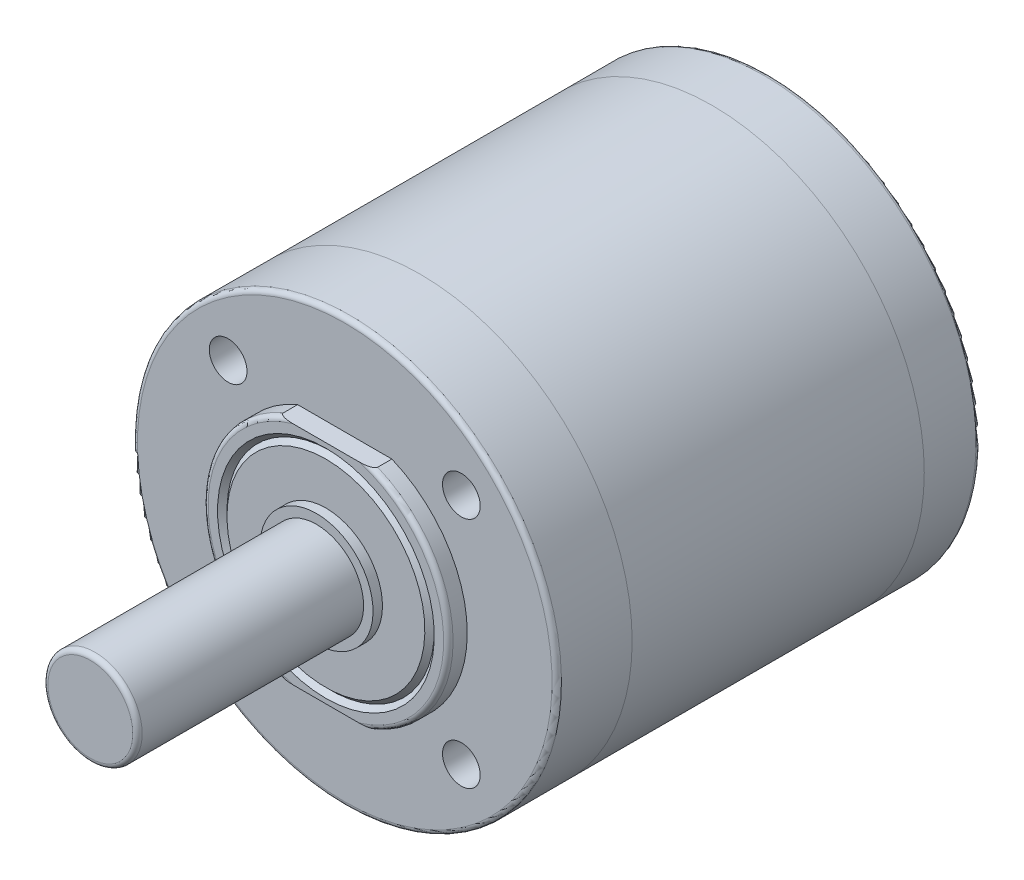
SolidWorks part; units mm, degrees
ref_plane "Front Plane" through (0, 0, 0) normal (0, 0, 1) x (1, 0, 0)
ref_plane "Top Plane" through (0, 0, 0) normal (0, 1, 0) x (1, 0, 0)
ref_plane "Right Plane" through (0, 0, 0) normal (1, 0, 0) x (0, 0, -1)
sketch "Sketch1" plane through (0, 0, 0) normal (1, 0, 0) x (0, 0, -1)
  line L0 (0, 0) -> (-72, 0) construction
  line L1 (0, 0) -> (0, 22.5)
  line L2 (0, 22.5) -> (-45, 22.5)
  line L3 (-45, 22.5) -> (-45, 13)
  line L4 (-45, 13) -> (-47, 13)
  line L5 (-47, 13) -> (-47, 11.5)
  line L6 (-48, 5) -> (-72, 5)
  line L7 (-72, 5) -> (-72, 0)
  line L8 (0, 0) -> (-72, 0)
  line L9 (-47, 11.5) -> (-46.5, 11)
  line L10 (-46.5, 11) -> (-47, 10.5)
  line L11 (-47, 6) -> (-48, 6)
  line L12 (-48, 6) -> (-48, 5)
  line L13 (-47, 10.5) -> (-47, 6)
  dimension "D1" = 45
  dimension "D2" = 22.5
  dimension "D3" = 25
  dimension "D4" = 2
  dimension "D5" = 13
  dimension "D6" = 5
  dimension "D7" = 1
  dimension "D8" = 1
  dimension "D9" = 11
  dimension "D10" = 0.5
  dimension "D11" = 135
revolve "Revolve1" add sketch "Sketch1" angle 360 about L0
sketch "Sketch2" plane through (0, 0, 0) normal (1, 0, 0) x (0, 0, -1)
  line L0 (-6, -22.5) -> (-6, 22.5)
  line L1 (-45, -22.5) -> (0, -22.5) construction
  line L2 (0, 22.5) -> (-45, 22.5) construction
  line L3 (-37, -22.5) -> (-37, 22.5)
  line L4 (-45, 22.5) -> (-45, -22.5) construction
  line L5 (0, -22.5) -> (0, 22.5) construction
  dimension "D1" = 8
  dimension "D2" = 6
split line "Split Line1"
fillet "Fillet1" radius 0.5 4 edges at (0, 22.5, 0) (0, 22.5, 45) (0, 13, 47) (0, 5, 72)
sketch "Sketch3" plane through (0, 0, 47) normal (0, 0, 1) x (1, 0, 0)
  line L0 (-5, 12) -> (5, 12)
  line L1 (0, 0) -> (-13, 0) construction
  line L2 (-5, -12) -> (5, -12)
  circle A1 centre (0, 0) radius 13 construction
  arc A2 (-5, -12) -> (5, -12) centre (0, 0) ccw
  arc A3 (5, 12) -> (-5, 12) centre (0, 0) ccw
  dimension "D1" = 24
extrude "Cut-Extrude1" cut sketch "Sketch3" against normal blind 2
sketch "Sketch4" plane through (0, 0, 45) normal (0, 0, 1) x (1, 0, 0)
  line L0 (-12.3744, 12.3744) -> (0, 0) construction
  line L1 (0, 0) -> (-22.5, 0) construction
  circle A0 centre (-12.3744, 12.3744) radius 2
  circle A1 centre (0, 0) radius 22.5 construction
  circle A2 centre (12.3744, 12.3744) radius 2
  circle A3 centre (12.3744, -12.3744) radius 2
  circle A4 centre (-12.3744, -12.3744) radius 2
  point P17 (0, 0)
  dimension "D2" = 4
  dimension "D1" = 45
  dimension "D3" = 17.5
  dimension "D4" = 4
extrude "Cut-Extrude2" cut sketch "Sketch4" against normal blind 8
